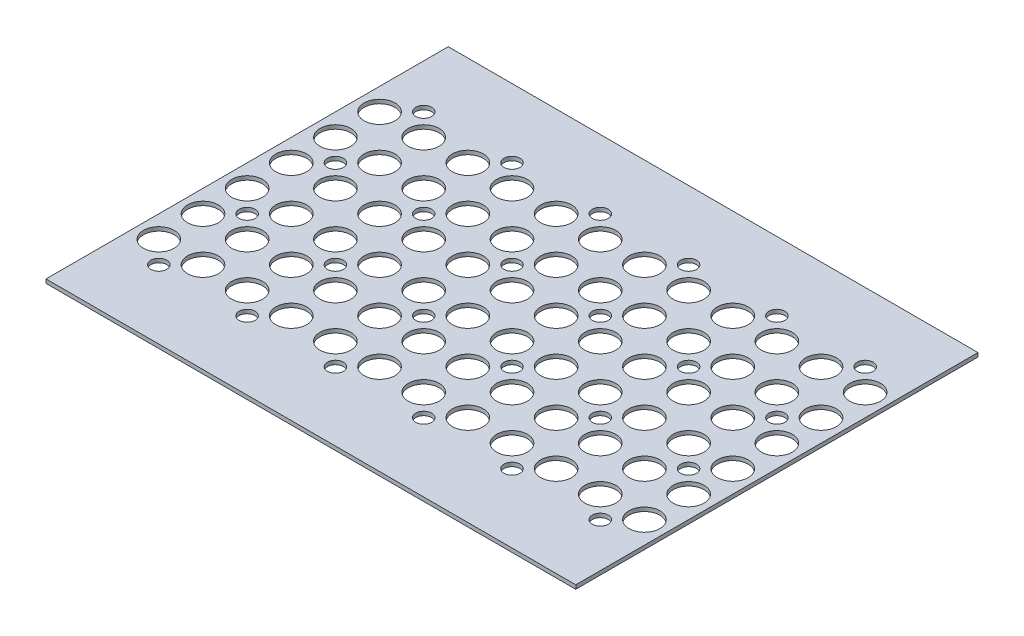
SolidWorks part; units mm, degrees
ref_plane "Front Plane" through (0, 0, 0) normal (0, 0, 1) x (1, 0, 0)
ref_plane "Top Plane" through (0, 0, 0) normal (0, 1, 0) x (1, 0, 0)
ref_plane "Right Plane" through (0, 0, 0) normal (1, 0, 0) x (0, 0, -1)
sketch "Sketch1" plane through (0, 0, 0) normal (0, 1, 0) x (1, 0, 0)
  line L0 (0, -55) -> (0, 55) construction
  line L1 (-54, -38.4841) -> (54, -38.4841)
  line L2 (-54, -38.4841) -> (-54, 43.5159)
  line L3 (-54, 43.5159) -> (54, 43.5159)
  line L4 (54, -38.4841) -> (54, 43.5159)
  line L5 (-54, -38.4841) -> (54, 43.5159) construction
  line L6 (-54, 43.5159) -> (54, -38.4841) construction
  circle A0 centre (-45, 29.5159) radius 1.625
  circle A98 centre (-49.5, 25.0159) radius 3.15
  circle A99 centre (-27, 29.5159) radius 1.625
  circle A100 centre (-9, 29.5159) radius 1.625
  circle A101 centre (9, 29.5159) radius 1.625
  circle A102 centre (27, 29.5159) radius 1.625
  circle A103 centre (45, 29.5159) radius 1.625
  circle A104 centre (-27, 11.5159) radius 1.625
  circle A105 centre (-9, 11.5159) radius 1.625
  circle A106 centre (9, 11.5159) radius 1.625
  circle A107 centre (27, 11.5159) radius 1.625
  circle A108 centre (45, 11.5159) radius 1.625
  circle A109 centre (-27, -6.4841) radius 1.625
  circle A110 centre (-9, -6.4841) radius 1.625
  circle A111 centre (9, -6.4841) radius 1.625
  circle A112 centre (27, -6.4841) radius 1.625
  circle A113 centre (45, -6.4841) radius 1.625
  circle A114 centre (-27, -24.4841) radius 1.625
  circle A115 centre (-9, -24.4841) radius 1.625
  circle A116 centre (9, -24.4841) radius 1.625
  circle A117 centre (27, -24.4841) radius 1.625
  circle A118 centre (45, -24.4841) radius 1.625
  circle A119 centre (-45, 11.5159) radius 1.625
  circle A120 centre (-45, -6.4841) radius 1.625
  circle A121 centre (-45, -24.4841) radius 1.625
  circle A122 centre (-40.5, 25.0159) radius 3.15
  circle A123 centre (-31.5, 25.0159) radius 3.15
  circle A124 centre (-22.5, 25.0159) radius 3.15
  circle A125 centre (-13.5, 25.0159) radius 3.15
  circle A126 centre (-4.5, 25.0159) radius 3.15
  circle A127 centre (4.5, 25.0159) radius 3.15
  circle A128 centre (13.5, 25.0159) radius 3.15
  circle A129 centre (22.5, 25.0159) radius 3.15
  circle A130 centre (31.5, 25.0159) radius 3.15
  circle A131 centre (40.5, 25.0159) radius 3.15
  circle A132 centre (49.5, 25.0159) radius 3.15
  circle A133 centre (-40.5, 16.0159) radius 3.15
  circle A134 centre (-31.5, 16.0159) radius 3.15
  circle A135 centre (-22.5, 16.0159) radius 3.15
  circle A136 centre (-13.5, 16.0159) radius 3.15
  circle A137 centre (-4.5, 16.0159) radius 3.15
  circle A138 centre (4.5, 16.0159) radius 3.15
  circle A139 centre (13.5, 16.0159) radius 3.15
  circle A140 centre (22.5, 16.0159) radius 3.15
  circle A141 centre (31.5, 16.0159) radius 3.15
  circle A142 centre (40.5, 16.0159) radius 3.15
  circle A143 centre (49.5, 16.0159) radius 3.15
  circle A144 centre (-40.5, 7.0159) radius 3.15
  circle A145 centre (-31.5, 7.0159) radius 3.15
  circle A146 centre (-22.5, 7.0159) radius 3.15
  circle A147 centre (-13.5, 7.0159) radius 3.15
  circle A148 centre (-4.5, 7.0159) radius 3.15
  circle A149 centre (4.5, 7.0159) radius 3.15
  circle A150 centre (13.5, 7.0159) radius 3.15
  circle A151 centre (22.5, 7.0159) radius 3.15
  circle A152 centre (31.5, 7.0159) radius 3.15
  circle A153 centre (40.5, 7.0159) radius 3.15
  circle A154 centre (49.5, 7.0159) radius 3.15
  circle A155 centre (-40.5, -1.9841) radius 3.15
  circle A156 centre (-31.5, -1.9841) radius 3.15
  circle A157 centre (-22.5, -1.9841) radius 3.15
  circle A158 centre (-13.5, -1.9841) radius 3.15
  circle A159 centre (-4.5, -1.9841) radius 3.15
  circle A160 centre (4.5, -1.9841) radius 3.15
  circle A161 centre (13.5, -1.9841) radius 3.15
  circle A162 centre (22.5, -1.9841) radius 3.15
  circle A163 centre (31.5, -1.9841) radius 3.15
  circle A164 centre (40.5, -1.9841) radius 3.15
  circle A165 centre (49.5, -1.9841) radius 3.15
  circle A166 centre (-40.5, -10.9841) radius 3.15
  circle A167 centre (-31.5, -10.9841) radius 3.15
  circle A168 centre (-22.5, -10.9841) radius 3.15
  circle A169 centre (-13.5, -10.9841) radius 3.15
  circle A170 centre (-4.5, -10.9841) radius 3.15
  circle A171 centre (4.5, -10.9841) radius 3.15
  circle A172 centre (13.5, -10.9841) radius 3.15
  circle A173 centre (22.5, -10.9841) radius 3.15
  circle A174 centre (31.5, -10.9841) radius 3.15
  circle A175 centre (40.5, -10.9841) radius 3.15
  circle A176 centre (49.5, -10.9841) radius 3.15
  circle A177 centre (-40.5, -19.9841) radius 3.15
  circle A178 centre (-31.5, -19.9841) radius 3.15
  circle A179 centre (-22.5, -19.9841) radius 3.15
  circle A180 centre (-13.5, -19.9841) radius 3.15
  circle A181 centre (-4.5, -19.9841) radius 3.15
  circle A182 centre (4.5, -19.9841) radius 3.15
  circle A183 centre (13.5, -19.9841) radius 3.15
  circle A184 centre (22.5, -19.9841) radius 3.15
  circle A185 centre (31.5, -19.9841) radius 3.15
  circle A186 centre (40.5, -19.9841) radius 3.15
  circle A187 centre (49.5, -19.9841) radius 3.15
  circle A188 centre (-49.5, 16.0159) radius 3.15
  circle A189 centre (-49.5, 7.0159) radius 3.15
  circle A190 centre (-49.5, -1.9841) radius 3.15
  circle A191 centre (-49.5, -10.9841) radius 3.15
  circle A192 centre (-49.5, -19.9841) radius 3.15
  point P0 (0, 2.5159)
  dimension "D3" = 3.25
  dimension "D4" = 14
  dimension "D5" = 9
  dimension "D8" = 18.5
  dimension "D10" = 6
  dimension "D7" = 6.3
  dimension "D15" = 4.5
  dimension "D1" = 108
  dimension "D2" = 82
  dimension "D6" = 1
  dimension "D11" = 1
  dimension "D12" = 4
  dimension "D13" = 12
  dimension "D14" = 6
extrude "Boss-Extrude1" add sketch "Sketch1" along normal blind 0.7937
